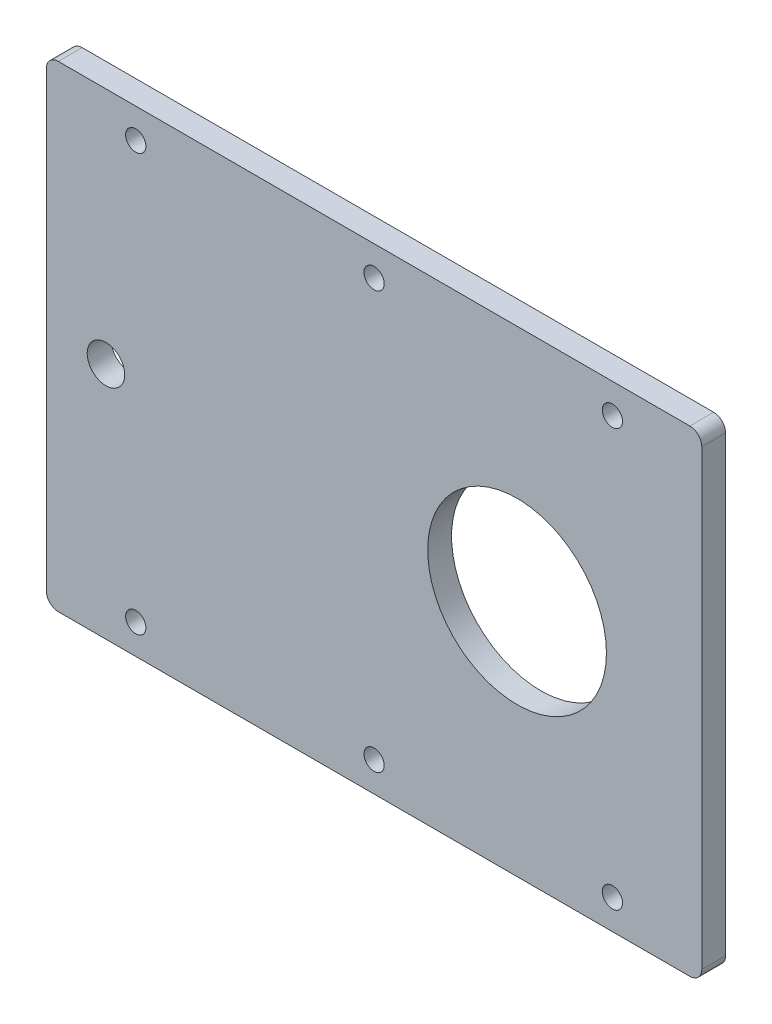
SolidWorks part; units mm, degrees
ref_plane "Front Plane" through (0, 0, 0) normal (0, 0, 1) x (1, 0, 0)
ref_plane "Top Plane" through (0, 0, 0) normal (0, 1, 0) x (1, 0, 0)
ref_plane "Right Plane" through (0, 0, 0) normal (1, 0, 0) x (0, 0, -1)
sketch "Sketch1" plane through (0, 0, 0) normal (0, 0, 1) x (1, 0, 0)
  line L1 (-1.1094, 38.5389) -> (108.8906, 38.5389)
  line L2 (-1.1094, 38.5389) -> (-1.1094, -41.4611)
  line L3 (-1.1094, -41.4611) -> (108.8906, -41.4611)
  line L4 (108.8906, 38.5389) -> (108.8906, -41.4611)
  circle A0 centre (13.8906, 33.5389) radius 1.7
  circle A1 centre (93.8906, 33.5389) radius 1.7
  circle A2 centre (53.8906, 33.5389) radius 1.7
  circle A3 centre (13.8906, -36.4611) radius 1.7
  circle A4 centre (53.8906, -36.4611) radius 1.7
  circle A5 centre (93.8906, -36.4611) radius 1.7
  circle A6 centre (8.8906, -1.4611) radius 3.15
  circle A7 centre (77.8906, -1.4611) radius 15
  point P29 (77.8906, -1.4611)
  dimension "D3" = 15
  dimension "D4" = 5
  dimension "D5" = 15
  dimension "D6" = 5
  dimension "D7" = 55
  dimension "D8" = 15
  dimension "D9" = 55
  dimension "D10" = 15
  dimension "D11" = 5
  dimension "D12" = 5
  dimension "D13" = 5
  dimension "D14" = 10
  dimension "D15" = 69
  dimension "D1" = 80
  dimension "D2" = 110
extrude "Boss-Extrude1" add sketch "Sketch1" along normal blind 4
fillet "Fillet1" radius 2 4 edges at (108.8906, -41.4611, 2) (-1.1094, -41.4611, 2) (-1.1094, 38.5389, 2) (108.8906, 38.5389, 2)
